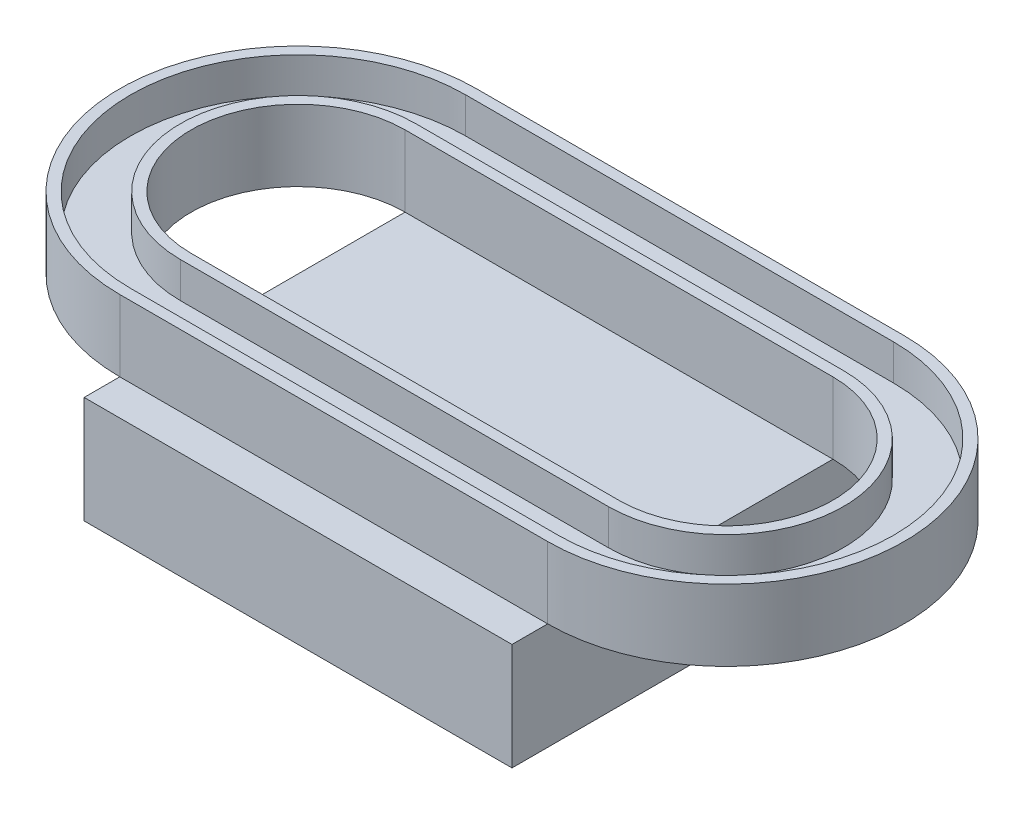
SolidWorks part; units mm, degrees
ref_plane "前基準面" through (0, 0, 0) normal (0, 0, 1) x (1, 0, 0)
ref_plane "上基準面" through (0, 0, 0) normal (0, 1, 0) x (1, 0, 0)
ref_plane "右基準面" through (0, 0, 0) normal (1, 0, 0) x (0, 0, -1)
sketch "草圖1" plane through (0, 0, 0) normal (0, 1, 0) x (1, 0, 0)
  line L0 (-60, 50) -> (60, 50)
  line L1 (-60, -50) -> (60, -50)
  line L2 (-60, -30) -> (60, -30)
  line L3 (-60, 30) -> (60, 30)
  arc A0 (60, 50) -> (60, -50) centre (60, 0) cw
  arc A1 (-60, 50) -> (-60, -50) centre (-60, 0) ccw
  arc A2 (-60, 30) -> (-60, -30) centre (-60, 0) ccw
  arc A3 (60, 30) -> (60, -30) centre (60, 0) cw
  point P6 (0, 50)
  dimension "D1" = 50
  dimension "D2" = 120
  dimension "D3" = 20
extrude "填料-伸長3" add sketch "草圖1" along normal blind 10
sketch "草圖4" plane through (0, 0, 0) normal (0, 1, 0) x (1, 0, 0)
  line L0 (-60, -50) -> (60, -50) construction
  line L1 (-60, -30) -> (60, -30) construction
  line L2 (-60, 30) -> (60, 30) construction
  line L3 (-60, 50) -> (60, 50) construction
  line L4 (-60, -50) -> (60, -50)
  line L5 (-60, -30) -> (60, -30)
  line L6 (-60, 30) -> (60, 30)
  line L7 (-60, 50) -> (60, 50)
  line L8 (-60, 33) -> (60, 33)
  line L9 (-60, -33) -> (60, -33)
  line L10 (-60, -47) -> (60, -47)
  line L11 (-60, 47) -> (60, 47)
  arc A0 (60, -50) -> (60, 50) centre (60, 0) ccw construction
  arc A1 (60, -30) -> (60, 30) centre (60, 0) ccw construction
  arc A2 (-60, 30) -> (-60, -30) centre (-60, 0) ccw construction
  arc A3 (-60, 50) -> (-60, -50) centre (-60, 0) ccw construction
  arc A4 (60, -50) -> (60, 50) centre (60, 0) ccw
  arc A5 (60, -30) -> (60, 30) centre (60, 0) ccw
  arc A6 (-60, 30) -> (-60, -30) centre (-60, 0) ccw
  arc A7 (-60, 50) -> (-60, -50) centre (-60, 0) ccw
  arc A8 (60, -33) -> (60, 33) centre (60, 0) ccw
  arc A9 (-60, 33) -> (-60, -33) centre (-60, 0) ccw
  arc A10 (-60, 47) -> (-60, -47) centre (-60, 0) ccw
  arc A11 (60, -47) -> (60, 47) centre (60, 0) ccw
  dimension "D1" = 3
  dimension "D2" = 3
extrude "填料-伸長4" add sketch "草圖4" along normal blind 20 contours L8 A9 L9 A8 A6 L6 A5 L5 | L7 A7 L4 A4 A11 L10 A10 L11
sketch "草圖6" plane through (0, 0, 0) normal (0, 1, 0) x (1, 0, 0)
  line L0 (-60, 50) -> (60, 50) construction
  line L1 (-60, -60) -> (60, -60)
  line L2 (-60, -60) -> (-60, 60)
  line L3 (-60, 60) -> (60, 60)
  line L4 (60, -60) -> (60, 60)
  line L5 (-60, -60) -> (60, 60) construction
  line L6 (-60, 60) -> (60, -60) construction
  point P0 (0, 0)
  dimension "D1" = 10
  dimension "D2" = 120
extrude "填料-伸長5" add sketch "草圖6" against normal blind 30
